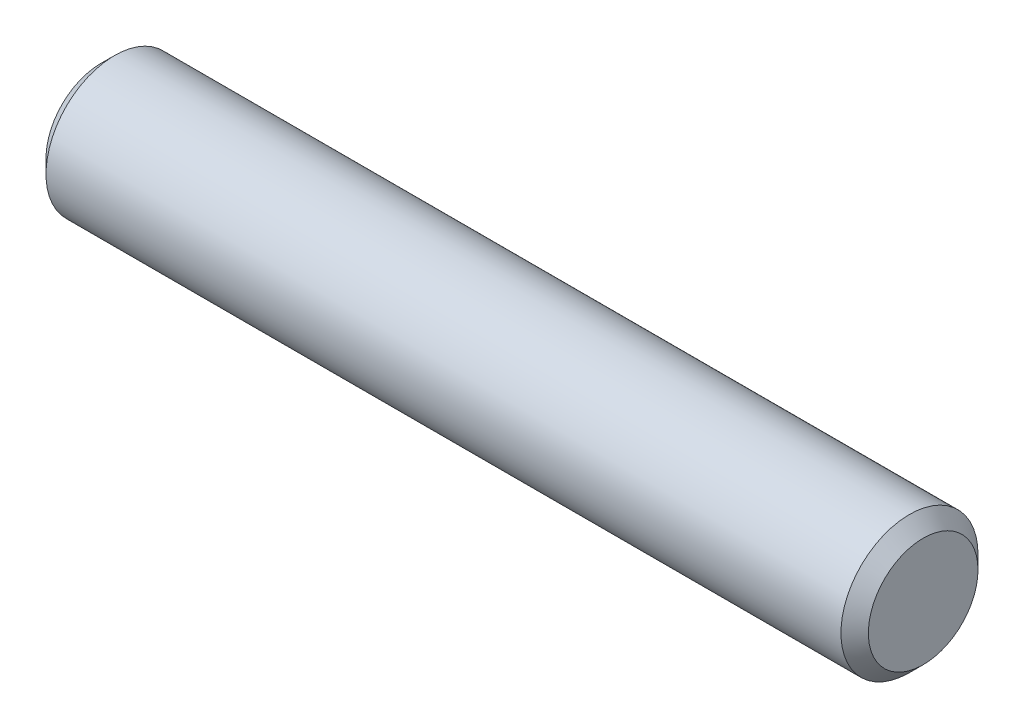
SolidWorks part; units mm, degrees
ref_plane "Front Plane" through (0, 0, 0) normal (0, 0, 1) x (1, 0, 0)
ref_plane "Top Plane" through (0, 0, 0) normal (0, 1, 0) x (1, 0, 0)
ref_plane "Right Plane" through (0, 0, 0) normal (1, 0, 0) x (0, 0, -1)
sketch "Sketch1" plane through (0, 0, 0) normal (1, 0, 0) x (0, 0, -1)
  circle A0 centre (0, 0) radius 2.5
  dimension "D1" = 5
extrude "Boss-Extrude1" add sketch "Sketch1" along normal blind 30 contours A0
chamfer "Chamfer1" distance 0.5 angle 45 2 edges at (30, 0, -2.5) (0, 0, -2.5)
